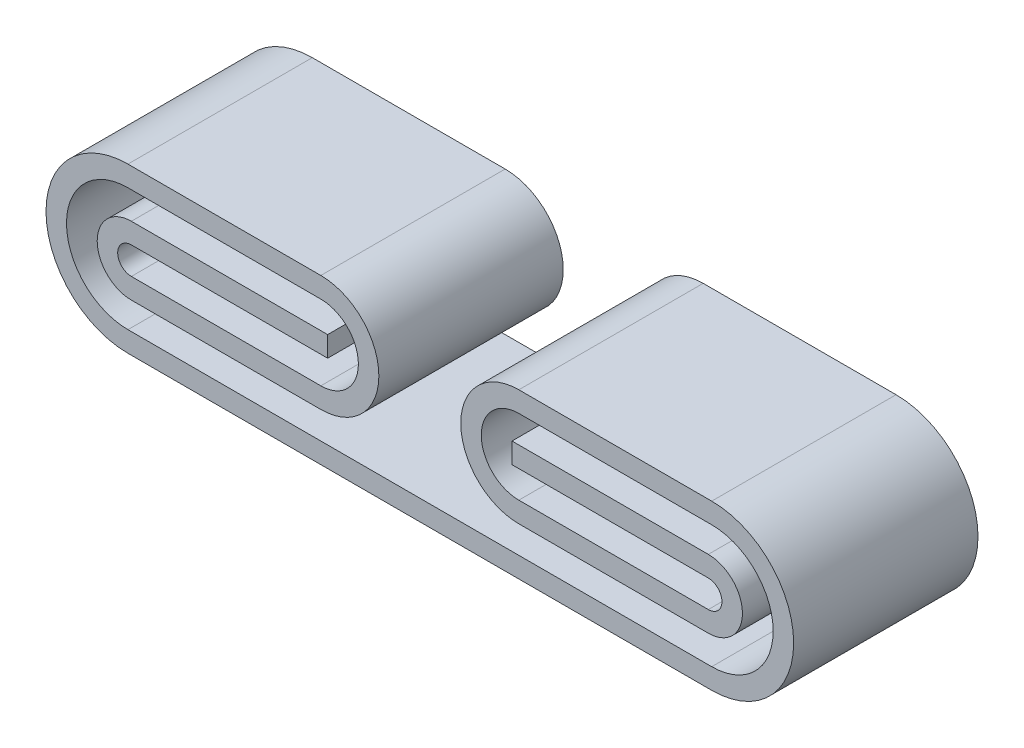
SolidWorks part; units mm, degrees
ref_plane "Front Plane" through (0, 0, 0) normal (0, 0, 1) x (1, 0, 0)
ref_plane "Top Plane" through (0, 0, 0) normal (0, 1, 0) x (1, 0, 0)
ref_plane "Right Plane" through (0, 0, 0) normal (1, 0, 0) x (0, 0, -1)
sketch "Sketch1" plane through (0, 0, 0) normal (0, 0, 1) x (1, 0, 0)
  line L0 (-17.25, 1) -> (0, 1)
  line L5 (-17.25, 1) -> (-17.25, 7)
  line L6 (-17.25, 7) -> (-3, 7)
  line L7 (-3, 7) -> (-3, 3.3333)
  line L8 (-3, 3.3333) -> (-14.75, 3.3333)
  line L9 (-18.25, 0) -> (0, 0)
  line L15 (-18.25, 0) -> (-18.25, 8)
  line L16 (-18.25, 8) -> (-2, 8)
  line L17 (-2, 8) -> (-2, 2.3333)
  line L18 (-2, 2.3333) -> (-15.75, 2.3333)
  line L20 (-15.75, 2.3333) -> (-15.75, 5.6667)
  line L21 (-15.75, 5.6667) -> (-4.5, 5.6667)
  line L22 (-4.5, 5.6667) -> (-4.5, 4.6667)
  line L23 (-4.5, 4.6667) -> (-14.75, 4.6667)
  line L24 (-14.75, 4.6667) -> (-14.75, 3.3333)
  line L25 (-17.25, 4) -> (-15.75, 4) construction
  line L26 (-4.5, 5.1667) -> (-3, 5.1667) construction
  line L27 (0, 8.8598) -> (0, -2.173) construction
  line L28 (0, 1) -> (0, 0)
  circle A0 centre (-14.0833, 4) radius 0.6667
  circle A1 centre (-14.0833, 4) radius 1.6667
  circle A2 centre (-4.8333, 5.1667) radius 2.8333
  circle A3 centre (-4.8333, 5.1667) radius 1.8333
  circle A4 centre (-14.25, 4) radius 3
  circle A5 centre (-14.25, 4) radius 4
  dimension "D1" = 1
  dimension "D2" = 1
  dimension "D3" = 1
  dimension "D4" = 1
  dimension "D5" = 1
  dimension "D6" = 1
  dimension "D7" = 1
  dimension "D8" = 18.25
  dimension "D9" = 8
  dimension "D10" = 2
  dimension "D11" = 1.5
extrude "Boss-Extrude2" add sketch "Sketch1" along normal blind 4 and the other way blind 5 contours A5 L9 L28 L0 | L0 A5 | L5 A5 L0 A4 | L5 A5 | L6 A5 L5 A4 | L6 A5 | A5 L6 A2 L16 | A2 L6 L7 L8 | A3 L7 L6 | A3 L8 L7 | A5 L18 A2 L8 | L18 A5 L8 A4 | L18 A4 L8 A1 | L23 A1 L8 L24 | A0 L23 L24 | A0 L24 L8 | A5 L23 A2 L21 | L23 A4 L21 A1 | L23 A5 L21 A4 | A3 L21 A2 L23 | L21 A3 L23 L22
mirror "Mirror1" about plane through (0, 0, 0) normal (1, 0, 0) of "Boss-Extrude2"
